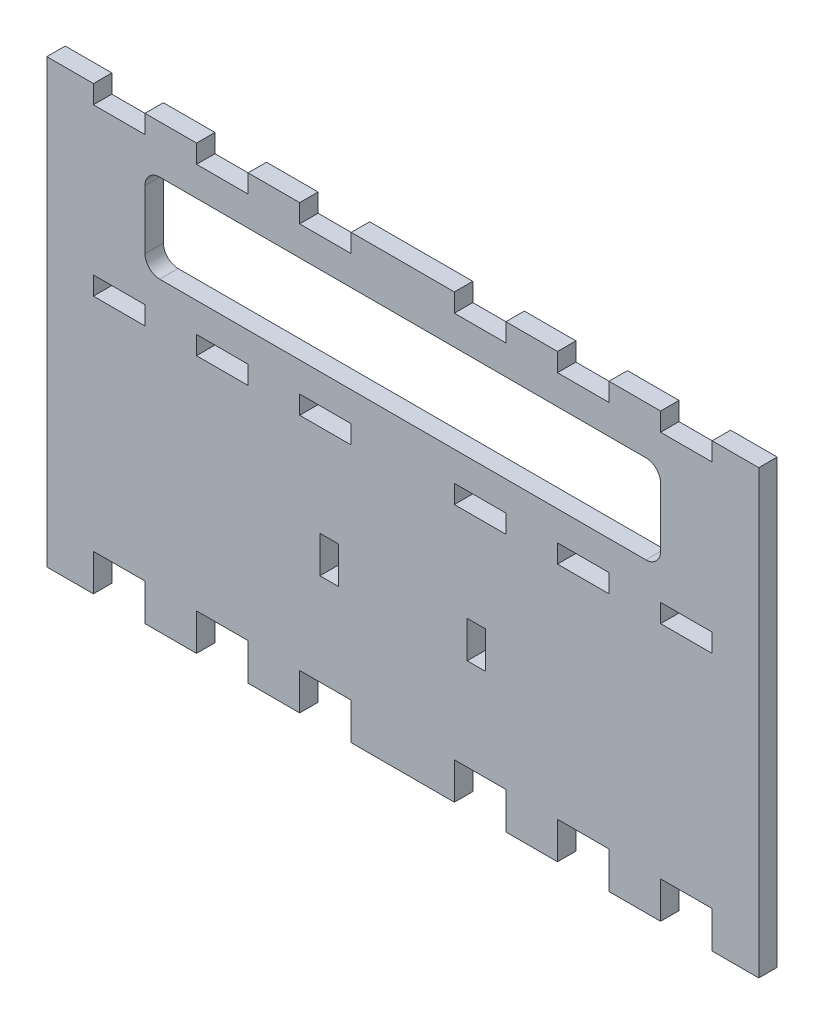
SolidWorks part; units mm, degrees
material "Beech"
ref_plane "Front" through (0, 0, 0) normal (0, 0, 1) x (1, 0, 0)
ref_plane "Top" through (0, 0, 0) normal (0, 1, 0) x (1, 0, 0)
ref_plane "Right" through (0, 0, 0) normal (1, 0, 0) x (0, 0, -1)
sketch "Sketch1" plane through (0, 0, 0) normal (0, 0, 1) x (1, 0, 0)
  line L0 (-48.325, -30) -> (-42, -30)
  line L1 (-48.325, -30) -> (48.325, -30) construction
  line L2 (-48.325, -30) -> (-48.325, 30)
  line L3 (-48.325, 30) -> (48.325, 30) construction
  line L4 (48.325, -30) -> (48.325, 30)
  line L5 (-48.325, -30) -> (48.325, 30) construction
  line L6 (-48.325, 30) -> (48.325, -30) construction
  line L7 (-42, -30) -> (-42, -25)
  line L8 (-42, -25) -> (-35, -25)
  line L9 (-35, -25) -> (-35, -30)
  line L10 (-35, -30) -> (-28, -30)
  line L11 (-28, -30) -> (-28, -25)
  line L12 (-28, -25) -> (-21, -25)
  line L13 (-21, -25) -> (-21, -30)
  line L14 (-21, -30) -> (-14, -30)
  line L15 (-14, -30) -> (-14, -25)
  line L16 (-14, -25) -> (-7, -25)
  line L17 (-7, -25) -> (-7, -30)
  line L18 (-7, -30) -> (7, -30)
  line L19 (7, -30) -> (7, -25)
  line L20 (7, -25) -> (14, -25)
  line L21 (14, -25) -> (14, -30)
  line L22 (14, -30) -> (21, -30)
  line L23 (21, -30) -> (21, -25)
  line L24 (21, -25) -> (28, -25)
  line L25 (28, -25) -> (28, -30)
  line L26 (28, -30) -> (35, -30)
  line L27 (35, -30) -> (35, -25)
  line L28 (35, -25) -> (42, -25)
  line L29 (42, -25) -> (42, -30)
  line L30 (42, -30) -> (48.325, -30)
  line L31 (48.325, 30) -> (42, 30)
  line L32 (42, 30) -> (42, 27.5)
  line L33 (42, 27.5) -> (35, 27.5)
  line L34 (35, 27.5) -> (35, 30)
  line L35 (35, 30) -> (28, 30)
  line L36 (28, 30) -> (28, 27.5)
  line L37 (28, 27.5) -> (21, 27.5)
  line L38 (21, 27.5) -> (21, 30)
  line L39 (21, 30) -> (14, 30)
  line L40 (14, 30) -> (14, 27.5)
  line L41 (14, 27.5) -> (7, 27.5)
  line L42 (7, 27.5) -> (7, 30)
  line L43 (7, 30) -> (-7, 30)
  line L44 (-7, 30) -> (-7, 27.5)
  line L45 (-7, 27.5) -> (-14, 27.5)
  line L46 (-14, 27.5) -> (-14, 30)
  line L47 (-14, 30) -> (-21, 30)
  line L48 (-21, 30) -> (-21, 27.5)
  line L49 (-21, 27.5) -> (-28, 27.5)
  line L50 (-28, 27.5) -> (-28, 30)
  line L51 (-28, 30) -> (-35, 30)
  line L52 (-35, 30) -> (-35, 27.5)
  line L53 (-35, 27.5) -> (-42, 27.5)
  line L54 (-42, 27.5) -> (-42, 30)
  line L55 (-42, 30) -> (-48.325, 30)
  line L56 (21, 5) -> (21, 7.5)
  line L57 (35, 5) -> (42, 5)
  line L58 (35, 5) -> (35, 7.5)
  line L59 (35, 7.5) -> (42, 7.5)
  line L60 (42, 5) -> (42, 7.5)
  line L61 (35, 5) -> (42, 7.5) construction
  line L62 (35, 7.5) -> (42, 5) construction
  line L63 (21, 5) -> (28, 5)
  line L64 (28, 5) -> (28, 7.5)
  line L65 (21, 7.5) -> (28, 7.5)
  line L66 (7, 5) -> (7, 7.5)
  line L67 (7, 5) -> (14, 5)
  line L68 (14, 5) -> (14, 7.5)
  line L69 (7, 7.5) -> (14, 7.5)
  line L70 (0, 4.2853) -> (0, -2.8641) construction
  line L71 (-35, 7.5) -> (-42, 7.5)
  line L72 (-42, 5) -> (-42, 7.5)
  line L73 (-35, 5) -> (-42, 5)
  line L74 (-35, 5) -> (-35, 7.5)
  line L75 (-21, 5) -> (-28, 5)
  line L76 (-28, 5) -> (-28, 7.5)
  line L77 (-21, 7.5) -> (-28, 7.5)
  line L78 (-21, 5) -> (-21, 7.5)
  line L79 (-7, 5) -> (-14, 5)
  line L80 (-14, 5) -> (-14, 7.5)
  line L81 (-7, 7.5) -> (-14, 7.5)
  line L82 (-7, 5) -> (-7, 7.5)
  line L83 (-8.75, -12.5) -> (-11.25, -12.5)
  line L84 (-33, 11.5) -> (33, 11.5)
  line L85 (-35, 13.5) -> (-35, 21.5)
  line L86 (-33, 23.5) -> (33, 23.5)
  line L87 (35, 13.5) -> (35, 21.5)
  line L88 (-35, 11.5) -> (35, 23.5) construction
  line L89 (-35, 23.5) -> (35, 11.5) construction
  line L90 (8.75, -12.5) -> (11.25, -12.5)
  line L91 (8.75, -12.5) -> (8.75, -7.5)
  line L92 (8.75, -7.5) -> (11.25, -7.5)
  line L93 (11.25, -12.5) -> (11.25, -7.5)
  line L94 (8.75, -12.5) -> (11.25, -7.5) construction
  line L95 (8.75, -7.5) -> (11.25, -12.5) construction
  line L96 (-11.25, -12.5) -> (-11.25, -7.5)
  line L97 (-8.75, -7.5) -> (-11.25, -7.5)
  line L98 (-8.75, -12.5) -> (-8.75, -7.5)
  arc A0 (33, 23.5) -> (35, 21.5) centre (33, 21.5) cw
  arc A1 (33, 11.5) -> (35, 13.5) centre (33, 13.5) ccw
  arc A2 (-33, 11.5) -> (-35, 13.5) centre (-33, 13.5) cw
  arc A3 (-35, 21.5) -> (-33, 23.5) centre (-33, 21.5) cw
  point P0 (0, 0)
  point P53 (38.5, 6.25)
  point P59 (28, 6.25)
  point P82 (0, 17.5)
  point P102 (10, -10)
  dimension "D13" = 2
  dimension "D1" = 96.65
  dimension "D2" = 60
  dimension "D3" = 7
  dimension "D4" = 14
  dimension "D5" = 5
  dimension "D6" = 2.5
  dimension "D7" = 35
  dimension "D9" = 7
  dimension "D10" = 10
  dimension "D11" = 70
  dimension "D12" = 12
  dimension "D14" = 5
  dimension "D15" = 2.5
  dimension "D16" = 15
  dimension "D17" = 17.5
  dimension "D8" = 3
extrude "Boss-Extrude1" add sketch "Sketch1" along normal blind 2.5
